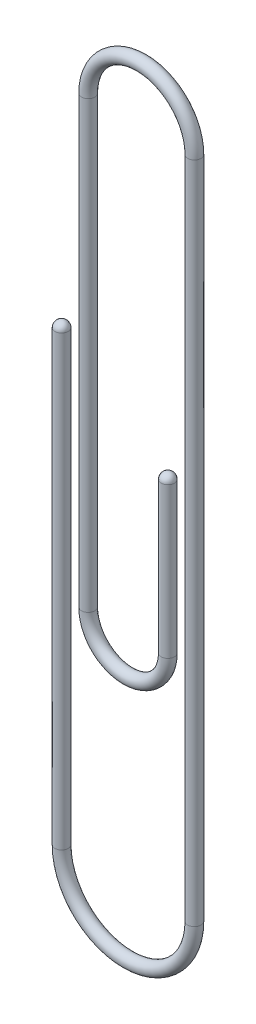
SolidWorks part; units mm, degrees
ref_plane "Alzado" through (0, 0, 0) normal (0, 0, 1) x (1, 0, 0)
ref_plane "Planta" through (0, 0, 0) normal (0, 1, 0) x (1, 0, 0)
ref_plane "Vista lateral" through (0, 0, 0) normal (1, 0, 0) x (0, 0, -1)
sketch "Croquis2" plane through (0, 0, 0) normal (0, 0, 1) x (1, 0, 0)
  line L0 (0, 1.6516) -> (0, -48.3484)
  line L1 (-8, 1.6516) -> (-8, -31.8534)
  line L2 (-2, -31.8534) -> (-2, -20.0269)
  line L3 (-10, -48.3484) -> (-10, -14.1342)
  arc A0 (0, 1.6516) -> (-8, 1.6516) centre (-4, 1.6516) ccw
  arc A1 (-8, -31.8534) -> (-2, -31.8534) centre (-5, -31.8534) ccw
  arc A2 (-10, -48.3484) -> (0, -48.3484) centre (-5, -48.3484) ccw
  dimension "D1" = 4
  dimension "D2" = 3
  dimension "D4" = 5
  dimension "D3" = 50
sweep "Barrer1" add path "Croquis2" circular profile diameter 1 parameters "D3"=1
fillet "Redondeo1" radius 0.5 1 edges at (-2, -20.0269, -0.5)
fillet "Redondeo2" radius 0.5 1 edges at (-10, -14.1342, -0.5)
